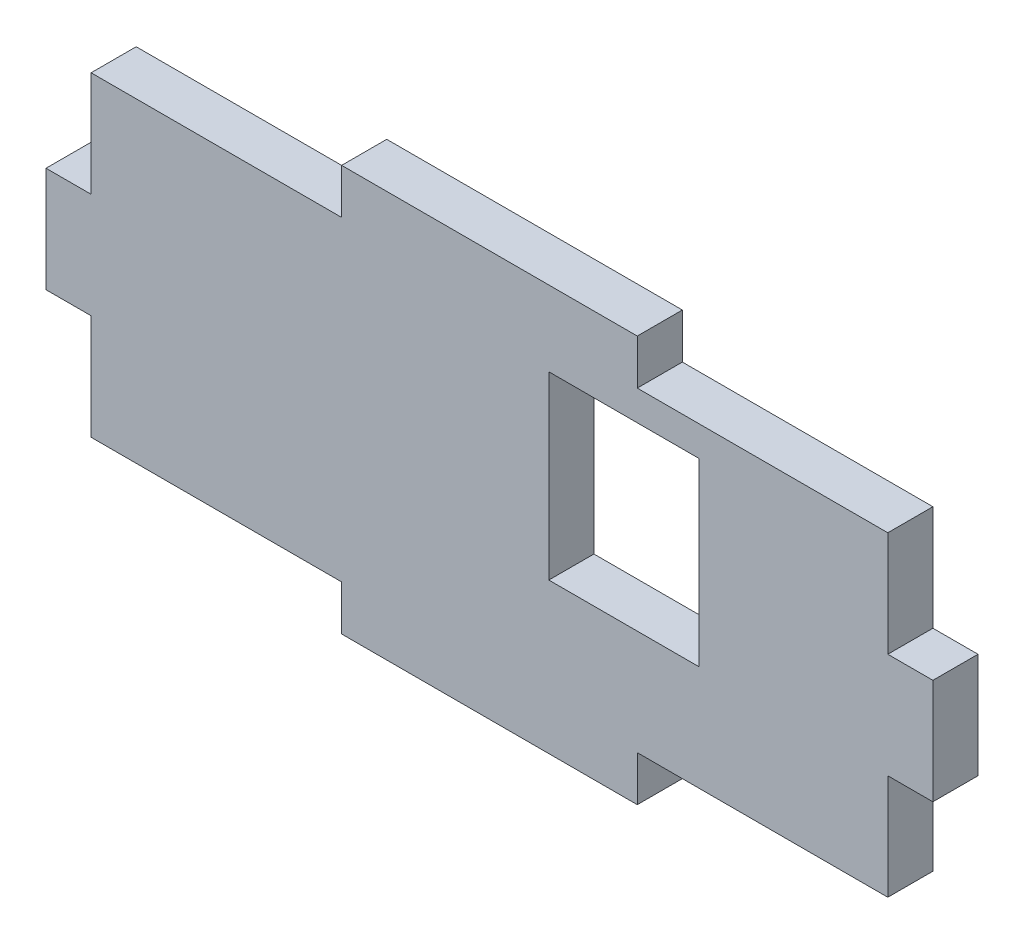
SolidWorks part; units mm, degrees
ref_plane "Front Plane" through (0, 0, 0) normal (0, 0, 1) x (1, 0, 0)
ref_plane "Top Plane" through (0, 0, 0) normal (0, 1, 0) x (1, 0, 0)
ref_plane "Right Plane" through (0, 0, 0) normal (1, 0, 0) x (0, 0, -1)
sketch "Sketch1" plane through (0, 0, 0) normal (0, 0, 1) x (1, 0, 0)
  line L0 (-26.5, 10.5) -> (-26.5, 3.5)
  line L1 (-26.5, 3.5) -> (-29.5, 3.5)
  line L2 (-29.5, 3.5) -> (-29.5, -3.5)
  line L3 (-29.5, -3.5) -> (-26.5, -3.5)
  line L4 (-26.5, -3.5) -> (-26.5, -10.5)
  line L5 (-26.5, -10.5) -> (-9.8333, -10.5)
  line L6 (-9.8333, -10.5) -> (-9.8333, -13.5)
  line L7 (-9.8333, -13.5) -> (9.8333, -13.5)
  line L8 (9.8333, -13.5) -> (9.8333, -10.5)
  line L9 (9.8333, -10.5) -> (26.5, -10.5)
  line L10 (0, -55) -> (0, 55) construction
  line L11 (26.5, -3.5) -> (26.5, -10.5)
  line L12 (29.5, -3.5) -> (26.5, -3.5)
  line L13 (29.5, 3.5) -> (29.5, -3.5)
  line L14 (26.5, 3.5) -> (29.5, 3.5)
  line L15 (26.5, 10.5) -> (26.5, 3.5)
  line L16 (55, 0) -> (-55, 0) construction
  line L17 (9.8333, 10.5) -> (26.5, 10.5)
  line L18 (9.8333, 13.5) -> (9.8333, 10.5)
  line L19 (-9.8333, 13.5) -> (9.8333, 13.5)
  line L20 (-9.8333, 10.5) -> (-9.8333, 13.5)
  line L21 (-26.5, 10.5) -> (-9.8333, 10.5)
  line L23 (3.95, -3.5) -> (13.95, -3.5)
  line L24 (3.95, -3.5) -> (3.95, 8.5)
  line L25 (3.95, 8.5) -> (13.95, 8.5)
  line L26 (13.95, -3.5) -> (13.95, 8.5)
  line L27 (3.95, -3.5) -> (13.95, 8.5) construction
  line L28 (3.95, 8.5) -> (13.95, -3.5) construction
  point P11 (0, 0)
  point P12 (-29.5, 0)
  point P14 (0, -13.5)
  point P28 (8.95, 2.5)
  point P34 (0, 0)
  dimension "D1" = 19.6667
  dimension "D2" = 21
  dimension "D3" = 3
  dimension "D4" = 16.6667
  dimension "D5" = 17.55
  dimension "D6" = 2
  dimension "D7" = 10
  dimension "D8" = 7
extrude "Boss-Extrude1" add sketch "Sketch1" along normal blind 3
